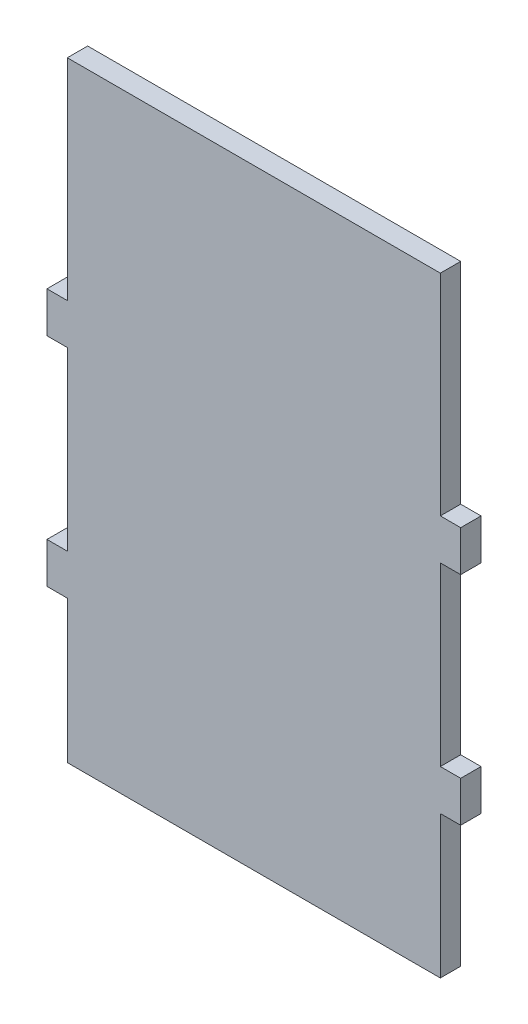
SolidWorks part; units mm, degrees
ref_plane "Přední rovina" through (0, 0, 0) normal (0, 0, 1) x (1, 0, 0)
ref_plane "Horní rovina" through (0, 0, 0) normal (0, 1, 0) x (1, 0, 0)
ref_plane "Pravá rovina" through (0, 0, 0) normal (1, 0, 0) x (0, 0, -1)
sketch "Skica1" plane through (0, 0, 0) normal (0, 0, 1) x (1, 0, 0)
  line L0 (0, 0) -> (55, 0)
  line L1 (0, 0) -> (0, -31)
  line L2 (55, 0) -> (55, -31)
  line L3 (0, -90) -> (55, -90)
  line L4 (0, -31) -> (-3, -31)
  line L5 (0, -37) -> (-3, -37)
  line L6 (-3, -31) -> (-3, -37)
  line L7 (0, -63) -> (-3, -63)
  line L8 (0, -69) -> (-3, -69)
  line L9 (-3, -63) -> (-3, -69)
  line L10 (55, -69) -> (58, -69)
  line L11 (58, -63) -> (58, -69)
  line L12 (55, -63) -> (58, -63)
  line L13 (55, -31) -> (58, -31)
  line L14 (55, -37) -> (58, -37)
  line L15 (58, -31) -> (58, -37)
  line L16 (55, -69) -> (55, -90)
  line L17 (55, -37) -> (55, -63)
  line L18 (0, -37) -> (0, -63)
  line L19 (0, -69) -> (0, -90)
  dimension "D1" = 55
  dimension "D2" = 90
  dimension "D3" = 3
  dimension "D4" = 3
  dimension "D5" = 6
  dimension "D6" = 6
  dimension "D7" = 31
  dimension "D8" = 26
  dimension "D9" = 6
  dimension "D10" = 6
  dimension "D11" = 31
  dimension "D12" = 26
  dimension "D13" = 3
  dimension "D14" = 3
extrude "Přidat vysunutím1" add sketch "Skica1" along normal blind 3
